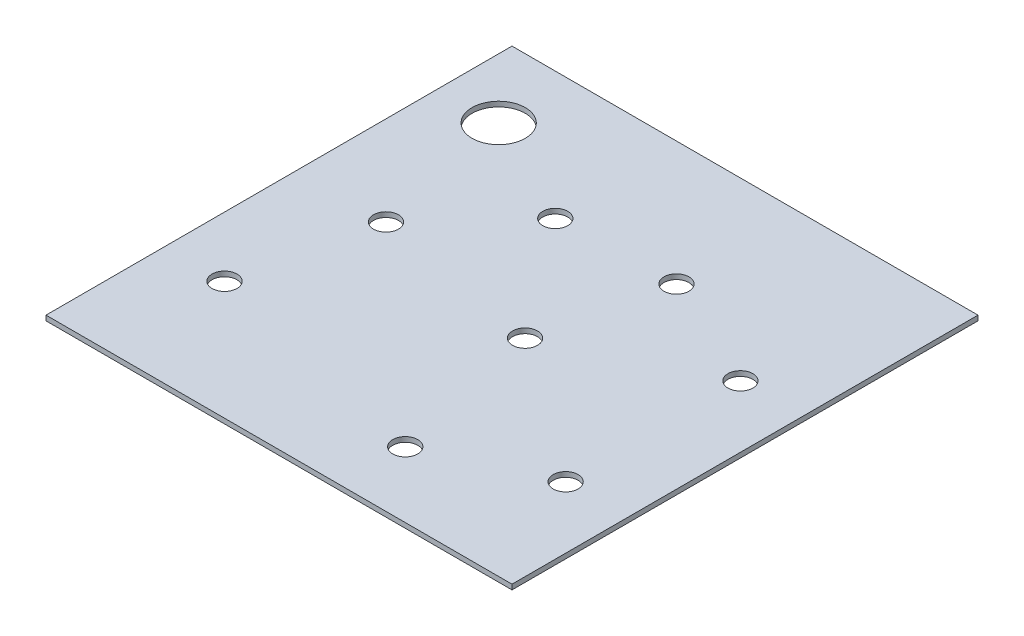
SolidWorks part; units mm, degrees
ref_plane "Front Plane" through (0, 0, 0) normal (0, 0, 1) x (1, 0, 0)
ref_plane "Top Plane" through (0, 0, 0) normal (0, 1, 0) x (1, 0, 0)
ref_plane "Right Plane" through (0, 0, 0) normal (1, 0, 0) x (0, 0, -1)
sketch "Sketch1" plane through (0, 0, 0) normal (0, 1, 0) x (1, 0, 0)
  line L1 (-140, -140) -> (140, -140)
  line L2 (-140, -140) -> (-140, 140)
  line L3 (-140, 140) -> (140, 140)
  line L4 (140, -140) -> (140, 140)
  line L5 (-140, -140) -> (140, 140) construction
  line L6 (-140, 140) -> (140, -140) construction
  circle A0 centre (-104, 96) radius 16
  circle A1 centre (-86.3455, 10.6301) radius 7.5
  circle A2 centre (-104, -68.7456) radius 7.5
  circle A3 centre (36.4243, -100.5577) radius 7.5
  circle A4 centre (15.8855, -8.0556) radius 7.5
  circle A5 centre (33.2267, 65.5847) radius 7.5
  circle A6 centre (102.8281, 34.4119) radius 7.5
  circle A7 centre (102.8281, -70.5987) radius 7.5
  circle A8 centre (-37.2961, 63.2893) radius 7.5
  point P0 (0, 0)
  point P22 (0, 0)
  point P27 (127.042, 122.7596)
  point P28 (124.8744, 124.8744)
  dimension "D2" = 32
  dimension "D3" = 36
  dimension "D4" = 44
  dimension "D5" = 15
  dimension "D1" = 280
extrude "Boss-Extrude1" add sketch "Sketch1" along normal mid plane 3
